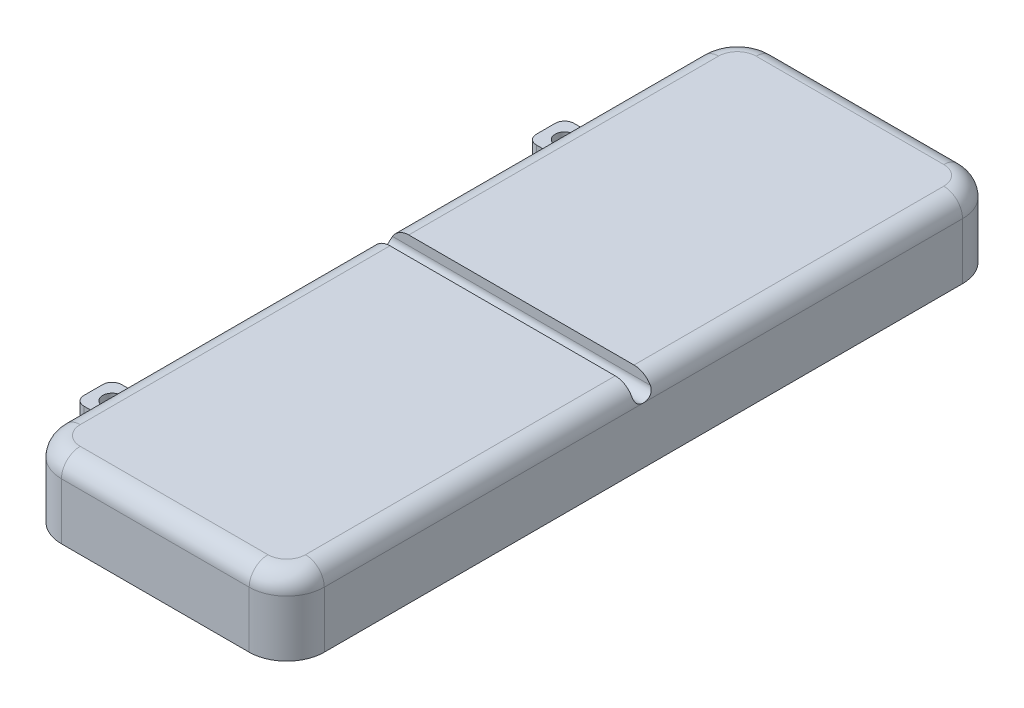
SolidWorks part; units mm, degrees
ref_plane "Front Plane" through (0, 0, 0) normal (0, 0, 1) x (1, 0, 0)
ref_plane "Top Plane" through (0, 0, 0) normal (0, 1, 0) x (1, 0, 0)
ref_plane "Right Plane" through (0, 0, 0) normal (1, 0, 0) x (0, 0, -1)
sketch "Sketch1" plane through (0, 0, 0) normal (0, 1, 0) x (1, 0, 0)
  line L3 (-58.1887, -33.5171) -> (5.3113, -33.5171)
  line L5 (-53.1087, 14.7429) -> (5.3113, 14.7429)
  line L13 (5.3113, 14.7429) -> (5.3113, -33.5171)
  line L27 (-58.1887, -5.4501) -> (-58.1887, -33.5171)
  line L31 (-58.1887, -0.3701) -> (-66.4437, -0.3701)
  line L32 (-66.4437, -0.3701) -> (-66.4437, -5.4501)
  line L33 (-66.4437, -5.4501) -> (-58.1887, -5.4501)
  line L34 (-58.1887, 9.6629) -> (-58.1887, -0.3701)
  arc A0 (-58.1887, 9.6629) -> (-53.1087, 14.7429) centre (-53.1087, 9.6629) cw
  dimension "D1" = 63.5
  dimension "D2" = 48.26
  dimension "D6" = 8.255
extrude "Boss-Extrude1" add sketch "Sketch1" along normal blind 10.16
sketch "Sketch3" plane through (0, 10.16, 0) normal (0, 1, 0) x (1, 0, 0)
  circle A0 centre (-63.9037, -2.9101) radius 1.27
extrude "Cut-Extrude1" cut sketch "Sketch3" against normal blind 10.16
sketch "Sketch4" plane through (0, 0, 5.4501) normal (0, 0, 1) x (1, 0, 0)
  line L0 (-66.4437, 10.16) -> (-66.4437, 2.54)
  line L1 (-66.4437, 10.16) -> (-66.4437, 0) construction
  line L2 (-66.4437, 2.54) -> (-58.1887, 2.54)
  line L3 (-58.1887, 10.16) -> (-58.1887, 0) construction
  line L4 (-58.1887, 2.54) -> (-58.1887, 10.16)
  line L5 (-58.1887, 10.16) -> (-66.4437, 10.16)
  dimension "D1" = 7.62
extrude "Cut-Extrude2" cut sketch "Sketch4" against normal blind 10.16
fillet "Fillet2" radius 0.508 3 edges at (-58.1887, 1.27, 5.4501) (-58.1887, 2.54, 2.9101) (-58.1887, 1.27, 0.3701)
fillet "Fillet3" radius 1.27 2 edges at (-66.4437, 1.27, 0.3701) (-66.4437, 1.27, 5.4501)
sketch "Sketch6" plane through (5.3113, 0, 0) normal (1, 0, 0) x (0, 0, -1)
  line L1 (31.9461, 22.6939) -> (-52.5495, 22.6939)
  line L2 (31.9461, 22.6939) -> (31.9461, -27.4886)
  line L3 (31.9461, -27.4886) -> (-52.5495, -27.4886)
  line L4 (-52.5495, 22.6939) -> (-52.5495, -27.4886)
extrude "Cut-Extrude3" cut sketch "Sketch6" against normal blind 27.94
sketch "Sketch7" plane through (0, 10.16, 0) normal (0, 1, 0) x (1, 0, 0)
  line L0 (-22.6287, 14.7429) -> (-27.7087, 14.7429)
  line L1 (-22.6287, 14.7429) -> (-53.1087, 14.7429) construction
  line L2 (-22.6287, 14.7429) -> (-22.6287, 9.6629)
  line L3 (-22.6287, -33.5171) -> (-22.6287, 14.7429) construction
  arc A0 (-22.6287, 9.6629) -> (-27.7087, 14.7429) centre (-27.7087, 9.6629) ccw
  dimension "D1" = 5.08
  dimension "D2" = 5.08
extrude "Cut-Extrude4" cut sketch "Sketch7" against normal blind 27.94
sketch "Sketch8" plane through (-58.1887, 0, 0) normal (-1, 0, 0) x (0, 0, 1)
  line L0 (33.5171, 10.16) -> (33.5171, 8.89)
  line L1 (33.5171, 10.16) -> (33.5171, 0) construction
  line L2 (33.5171, 8.89) -> (33.5171, 7.62)
  line L3 (32.2471, 8.89) -> (32.2471, 10.16)
  line L4 (-9.6629, 10.16) -> (33.5171, 10.16) construction
  line L5 (32.2471, 10.16) -> (33.5171, 10.16)
  arc A0 (32.2471, 8.89) -> (33.5171, 7.62) centre (33.5171, 8.89) ccw
  dimension "D2" = 1.27
  dimension "D1" = 1.27
extrude "Cut-Extrude5" cut sketch "Sketch8" against normal blind 40.132
fillet "Fillet4" radius 2.54 5 edges at (-24.1166, 10.16, -13.255) (-22.6287, 10.16, 11.2921) (-40.4087, 10.16, -14.7429) (-56.7008, 10.16, -13.255) (-58.1887, 10.16, 11.2921)
mirror "Mirror1" about plane through (-58.1887, 10.16, 33.5171) normal (0, 0, -1) of "Fillet4", "Cut-Extrude5", "Cut-Extrude4", "Cut-Extrude3", "Fillet3", "Fillet2", "Cut-Extrude2", "Cut-Extrude1", "Boss-Extrude1"
